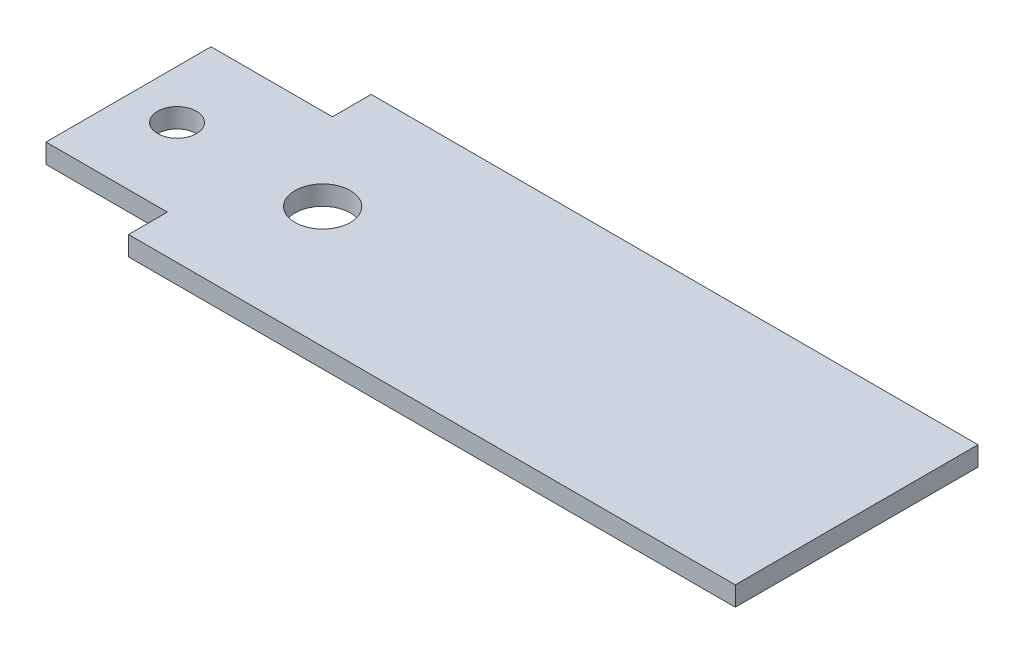
SolidWorks part; units mm, degrees
material "ABS PC"
ref_plane "Front Plane" through (0, 0, 0) normal (0, 0, 1) x (1, 0, 0)
ref_plane "Top Plane" through (0, 0, 0) normal (0, 1, 0) x (1, 0, 0)
ref_plane "Right Plane" through (0, 0, 0) normal (1, 0, 0) x (0, 0, -1)
sketch "Sketch1" plane through (0, 0, 0) normal (0, 1, 0) x (1, 0, 0)
  line L1 (-75, 25) -> (75, 25)
  line L2 (-75, 25) -> (-75, -25)
  line L3 (-75, -25) -> (75, -25)
  line L4 (75, 25) -> (75, -25)
  line L5 (-75, 25) -> (75, -25) construction
  line L6 (-75, -25) -> (75, 25) construction
  point P0 (0, 0)
  dimension "D1" = 150
  dimension "D2" = 50
extrude "Boss-Extrude1" add sketch "Sketch1" along normal blind 4
sketch "Sketch2" plane through (0, 0, 0) normal (0, -1, 0) x (1, 0, 0)
  line L0 (-75, -25) -> (-75, 25) construction
  circle A0 centre (-65, 0) radius 4
  circle A1 centre (-35, 0) radius 5.7
  dimension "D1" = 10
  dimension "D2" = 30
  dimension "D3" = 11.4
extrude "Cut-Extrude1" cut sketch "Sketch2" against normal blind 4
sketch "Sketch3" plane through (0, 4, 0) normal (0, 1, 0) x (1, 0, 0)
  line L1 (-75, 25) -> (-50, 25)
  line L2 (-75, 25) -> (-75, 17)
  line L3 (-75, 17) -> (-50, 17)
  line L4 (-50, 25) -> (-50, 17)
  line L5 (-75, -25) -> (-50, -25)
  line L6 (-75, -25) -> (-75, -17)
  line L7 (-75, -17) -> (-50, -17)
  line L8 (-50, -25) -> (-50, -17)
  dimension "D1" = 8
  dimension "D2" = 25
  dimension "D3" = 25
  dimension "D4" = 8
extrude "Cut-Extrude2" cut sketch "Sketch3" against normal blind 4
sketch "Sketch4" plane through (75, 0, 0) normal (1, 0, 0) x (0, 0, -1)
  line L0 (-25, 0) -> (25, 0)
  line L2 (-25, 0) -> (-35, 17.3205)
  line L3 (-25, 4) -> (-25, 0) construction
  line L4 (0, 0) -> (0, 14.4172) construction
  line L5 (25, 0) -> (35, 17.3205)
  line L6 (22.6906, 4) -> (31.5359, 19.3205)
  line L7 (-22.6906, 4) -> (22.6906, 4)
  line L8 (-22.6906, 4) -> (-31.5359, 19.3205)
  line L9 (35, 17.3205) -> (31.5359, 19.3205)
  line L10 (-35, 17.3205) -> (-31.5359, 19.3205)
  point P6 (0, 0)
  dimension "D1" = 30
  dimension "D2" = 20
  dimension "D3" = 4
extrude "Boss-Extrude2" [suppressed] add sketch "Sketch4" against normal blind 30
